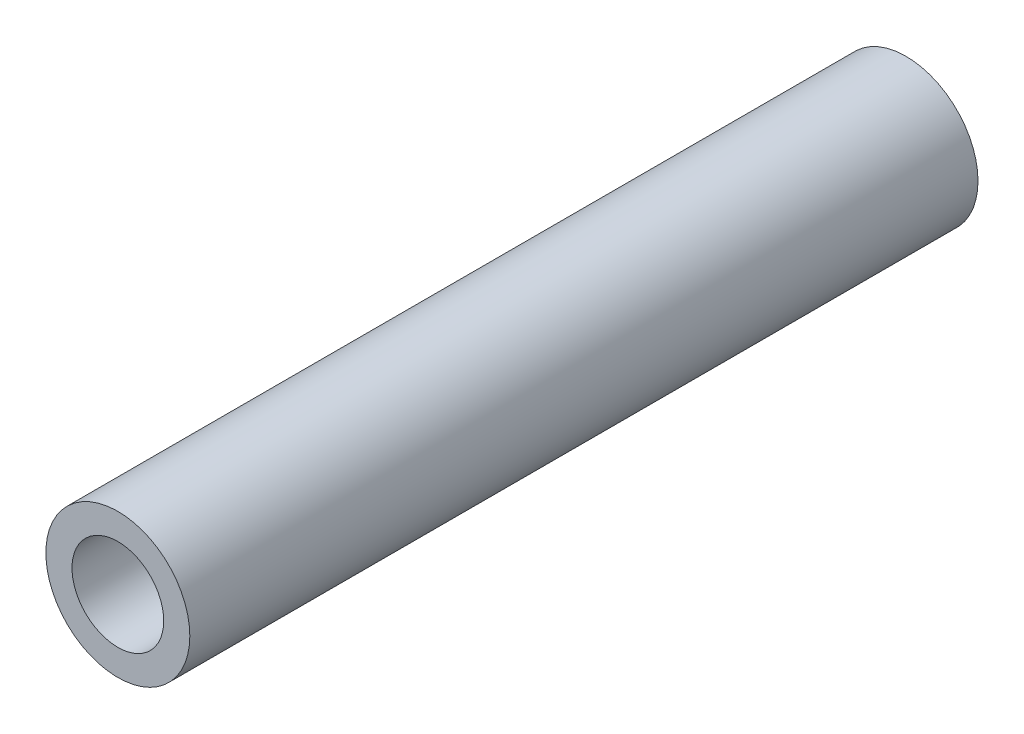
SolidWorks part; units mm, degrees
ref_plane "Front Plane" through (0, 0, 0) normal (0, 0, 1) x (1, 0, 0)
ref_plane "Top Plane" through (0, 0, 0) normal (0, 1, 0) x (1, 0, 0)
ref_plane "Right Plane" through (0, 0, 0) normal (1, 0, 0) x (0, 0, -1)
sketch "S01 - Open steel core bore" plane through (0, 0, 0) normal (0, 0, 1) x (1, 0, 0)
  circle A0 centre (0, 0) radius 2.7
  circle A1 centre (0, 0) radius 1.72
  dimension "D1" = 3.44
  dimension "D2" = 5.4
extrude "01 - Open steel core bore" add sketch "S01 - Open steel core bore" along normal blind 29.5649
